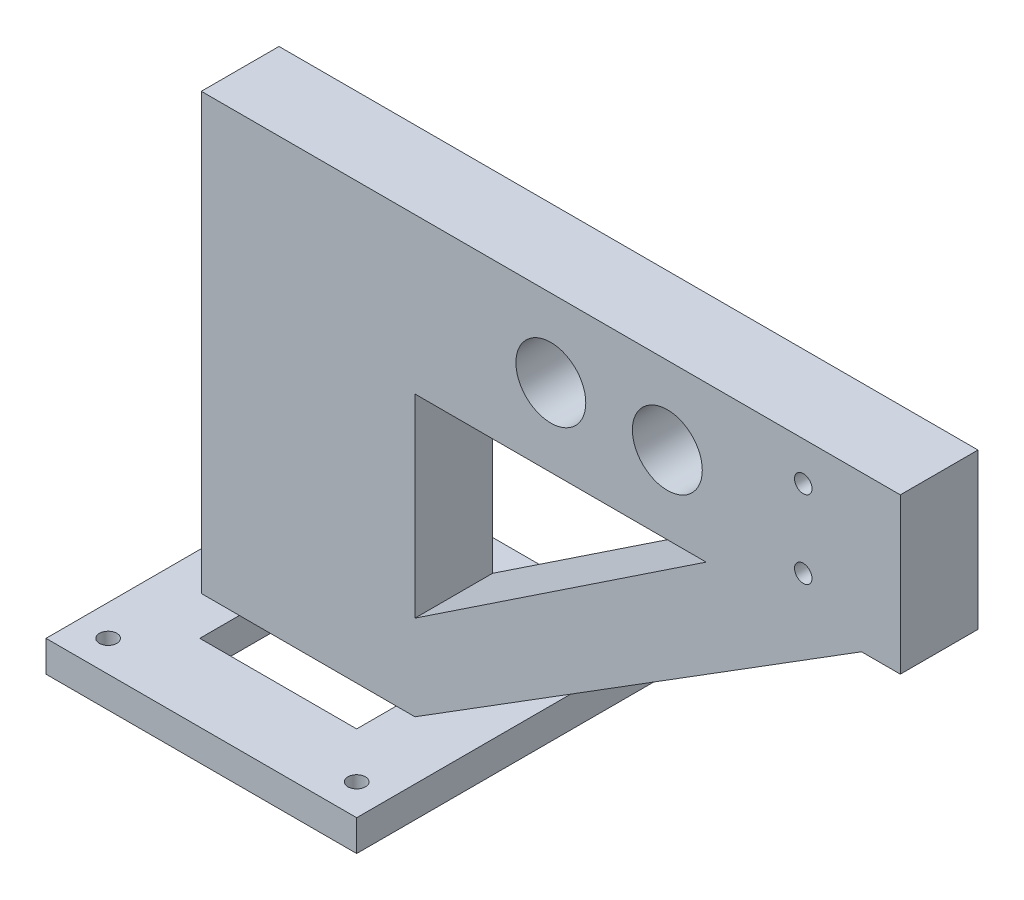
SolidWorks part; units mm, degrees
ref_plane "前视基准面" through (0, 0, 0) normal (0, 0, 1) x (1, 0, 0)
ref_plane "上视基准面" through (0, 0, 0) normal (0, 1, 0) x (1, 0, 0)
ref_plane "右视基准面" through (0, 0, 0) normal (1, 0, 0) x (0, 0, -1)
other "Configuration Table"
sketch "草图1" plane through (0, 0, 0) normal (0, 1, 0) x (1, 0, 0)
  line L1 (-40, -40) -> (40, -40)
  line L2 (-40, -40) -> (-40, 40)
  line L3 (-40, 40) -> (40, 40)
  line L4 (40, -40) -> (40, 40)
  line L6 (-20.2, -20.2) -> (20.2, -20.2)
  line L7 (-20.2, -20.2) -> (-20.2, 20.2)
  line L8 (-20.2, 20.2) -> (20.2, 20.2)
  line L9 (20.2, -20.2) -> (20.2, 20.2)
extrude "立柱顶部安装环" add sketch "草图1" along normal blind 8
sketch "草图2" plane through (0, 0, 0) normal (0, 0, 1) x (1, 0, 0)
  line L0 (-30, 8) -> (25, 8)
  line L1 (25, 8) -> (140, 80)
  line L2 (140, 80) -> (150, 80)
  line L3 (150, 80) -> (150, 120)
  line L4 (150, 120) -> (-30, 120)
  line L5 (-30, 120) -> (-30, 8)
extrude "一体三角撑与后臂" add sketch "草图2" along normal blind 20 from offset 10
sketch "草图3" plane through (0, 0, 0) normal (0, 0, 1) x (1, 0, 0)
  line L0 (25, 30) -> (100, 80)
  line L1 (100, 80) -> (25, 80)
  line L2 (25, 80) -> (25, 30)
extrude "三角减重窗口" cut sketch "草图3" against normal through all and the other way through all
sketch "草图4" plane through (0, 0, 0) normal (0, 0, 1) x (1, 0, 0)
  circle A0 centre (60, 100) radius 9
  circle A1 centre (90, 100) radius 9
extrude "后臂减重孔" cut sketch "草图4" against normal through all and the other way through all
sketch "草图5" plane through (0, 0, 0) normal (0, 0, 1) x (1, 0, 0)
  circle A0 centre (125, 90) radius 2.25
  circle A1 centre (125, 110) radius 2.25
extrude "悬臂拼接M4" cut sketch "草图5" against normal through all and the other way through all
sketch "草图6" plane through (0, 0, 0) normal (0, 1, 0) x (1, 0, 0)
  circle A0 centre (-32, -32) radius 2.25
  circle A1 centre (-32, 32) radius 2.25
  circle A2 centre (32, -32) radius 2.25
  circle A3 centre (32, 32) radius 2.25
extrude "柱顶四个M4" cut sketch "草图6" against normal through all and the other way through all
